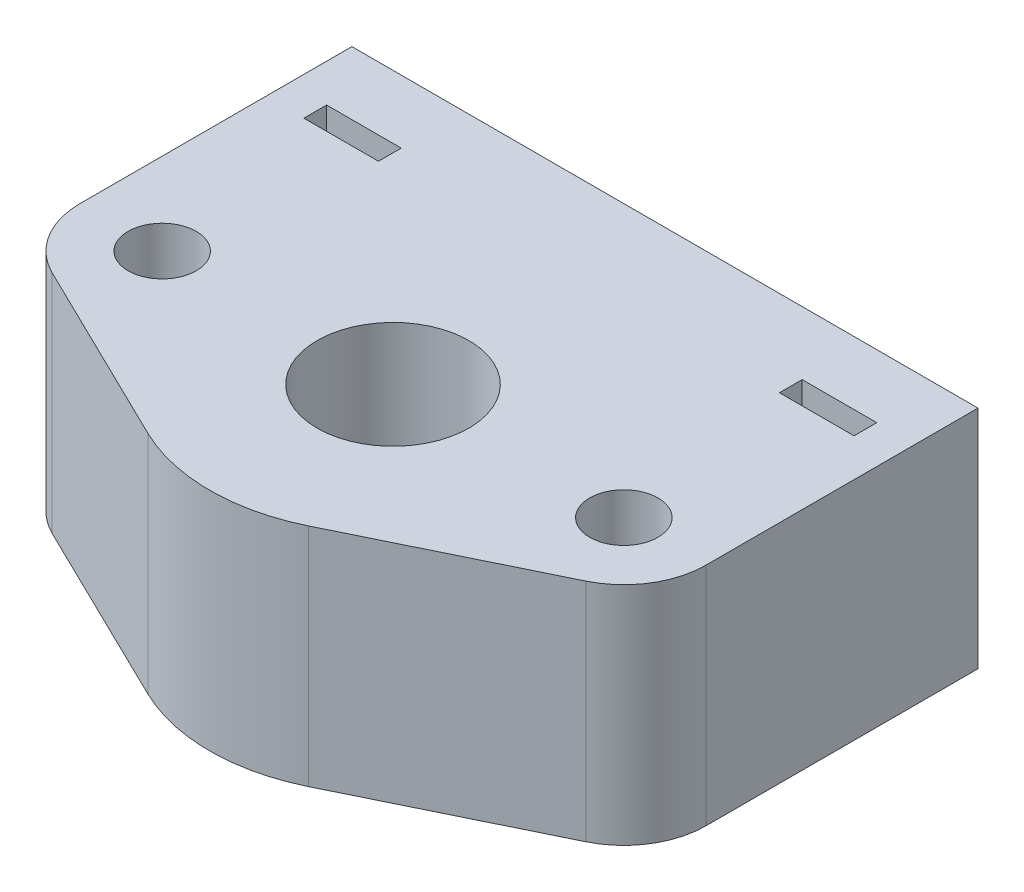
SolidWorks part; units mm, degrees
ref_plane "Front Plane" through (0, 0, 0) normal (0, 0, 1) x (1, 0, 0)
ref_plane "Top Plane" through (0, 0, 0) normal (0, 1, 0) x (1, 0, 0)
ref_plane "Right Plane" through (0, 0, 0) normal (1, 0, 0) x (0, 0, -1)
sketch "Sketch1" plane through (0, 0, 0) normal (0, 1, 0) x (1, 0, 0)
  line L0 (-24.75, 0) -> (-24.75, -21.5)
  line L2 (-24.75, 0) -> (0, 0)
  line L3 (0, 0) -> (0, -15.5)
  line L4 (0, -27.5) -> (0, -36)
  line L7 (-21.0993, -27.3422) -> (-6.3562, -34.5326)
  line L9 (-18.25, -21.5) -> (0, -21.5) construction
  circle A0 centre (-18.25, -21.5) radius 2.7
  arc A1 (0, -15.5) -> (0, -27.5) centre (0, -21.5) ccw
  arc A2 (-6.3562, -34.5326) -> (0, -36) centre (0, -21.5) ccw
  arc A3 (-24.75, -21.5) -> (-21.0993, -27.3422) centre (-18.25, -21.5) ccw
  dimension "D3" = 6
  dimension "D6" = 14.5
  dimension "D7" = 6.5
  dimension "D2" = 5.4
  dimension "D1" = 21.5
  dimension "D8" = 18.25
extrude "Boss-Extrude1" add sketch "Sketch1" along normal blind 11.9 and the other way blind 5.95
sketch "Sketch3" plane through (0, 0, 0) normal (0, 0, -1) x (-1, 0, 0)
  line L0 (0, -5.95) -> (0, 11.9) construction
  line L2 (18.8, 11.9) -> (18.8, 5.95) construction
  line L3 (0, 11.9) -> (24.75, 11.9) construction
  line L4 (18.8, 5.95) -> (24.75, 5.95) construction
  line L5 (24.75, 11.9) -> (24.75, -5.95) construction
  line L6 (0, 1.7) -> (0, -1.7)
  circle A0 centre (18.8, 5.95) radius 1.7
  arc A1 (0, 1.7) -> (0, -1.7) centre (0, 0) cw
  dimension "D1" = 3.4
  dimension "D2" = 5.95
extrude "Cut-Extrude1" cut sketch "Sketch3" against normal blind 10
sketch "Sketch4" plane through (0, 0, 0) normal (0, 0, -1) x (-1, 0, 0)
  line L0 (15.85, 8.9) -> (15.85, 11.9)
  line L1 (15.85, 3) -> (21.75, 3)
  line L2 (15.85, 3) -> (15.85, 8.9)
  line L3 (15.85, 8.9) -> (21.75, 8.9) construction
  line L4 (21.75, 3) -> (21.75, 8.9)
  line L5 (15.85, 3) -> (21.75, 8.9) construction
  line L6 (15.85, 8.9) -> (21.75, 3) construction
  line L7 (0, 11.9) -> (24.75, 11.9) construction
  line L8 (21.75, 8.9) -> (21.75, 11.9)
  line L9 (21.75, 11.9) -> (15.85, 11.9)
  line L10 (0, 2.95) -> (2.95, 2.95)
  line L11 (0, 1.7) -> (0, 11.9) construction
  line L12 (2.95, 2.95) -> (2.95, 0)
  line L13 (0, -5.95) -> (24.75, -5.95) construction
  line L14 (2.95, -5.95) -> (0, -5.95)
  line L15 (0, -5.95) -> (0, 2.95)
  line L16 (2.95, 0) -> (2.95, -5.95)
  line L17 (0, 0) -> (2.95, 0) construction
  point P0 (18.8, 5.95)
  dimension "D1" = 5.9
  dimension "D2" = 2.95
extrude "Cut-Extrude2" cut sketch "Sketch4" against normal blind 1.8 from offset 5 offset against normal yes
sketch "Sketch6" plane through (0, -5.95, 0) normal (0, -1, 0) x (1, 0, 0)
  line L1 (-14, 23.9537) -> (-18.25, 26.4075)
  line L2 (-18.25, 26.4075) -> (-22.5, 23.9537)
  line L3 (-22.5, 23.9537) -> (-22.5, 19.0463)
  line L4 (-22.5, 19.0463) -> (-18.25, 16.5925)
  line L5 (-18.25, 16.5925) -> (-14, 19.0463)
  line L6 (-14, 19.0463) -> (-14, 23.9537)
  circle A0 centre (-18.25, 21.5) radius 4.25 construction
  dimension "D1" = 8.5
extrude "Cut-Extrude3" cut sketch "Sketch6" against normal blind 10
mirror "Mirror1" about plane through (0, -5.95, 0) normal (1, 0, 0) of bodies 108 103
equation "\"M3_d\"= 3.4"
equation "\"M3_nut_m\"= 1.8"
equation "\"M3_nut_s\"= 5.9"
equation "\"t\"= 3"
equation "\"D1@Boss-Extrude1\"=\"M3_nut_s\" + 2 * \"t\""
equation "\"D1@Sketch3\"=\"M3_d\""
equation "\"D1@Sketch4\"=\"M3_nut_s\""
equation "\"D1@Cut-Extrude2\"=\"M3_nut_m\""
equation "\"D2@Sketch3\"=\"M3_nut_s\" / 2 + \"t\""
equation "\"D19@Cut-Extrude5\"=(10 - \"M3_nut_m\") / 2"
equation "\"D2@Boss-Extrude1\"=0.5 * \"M3_nut_s\" + \"t\""
equation "\"D2@Sketch4\"=\"M3_nut_s\" / 2"
equation "\"M5_d\"= 5.4"
equation "\"D2@Sketch1\"=\"M5_d\""
equation "\"M5_nut_s\"= 8.5"
equation "\"D1@Sketch6\"=\"M5_nut_s\""
